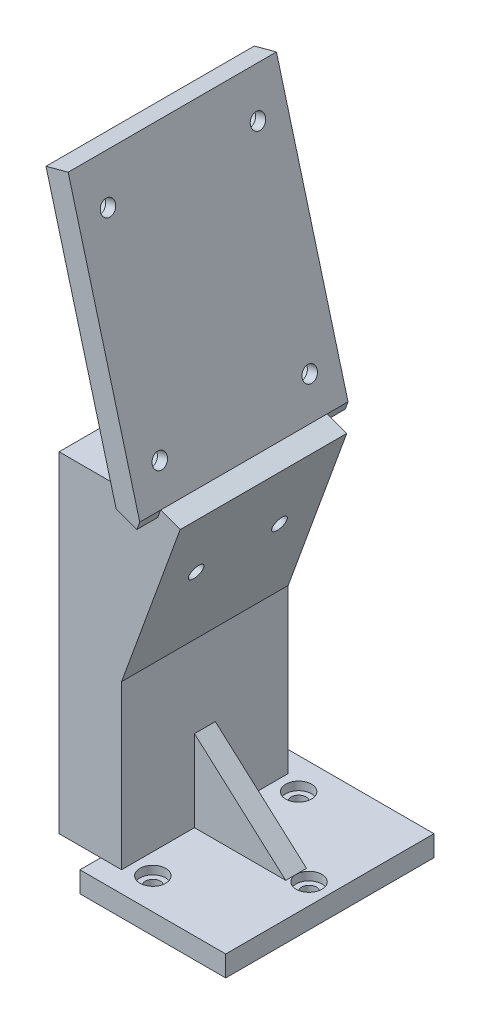
SolidWorks part; units mm, degrees
ref_plane "前视基准面" through (0, 0, 0) normal (0, 0, 1) x (1, 0, 0)
ref_plane "上视基准面" through (0, 0, 0) normal (0, 1, 0) x (1, 0, 0)
ref_plane "右视基准面" through (0, 0, 0) normal (1, 0, 0) x (0, 0, -1)
other "Configuration Table"
sketch "草图1" plane through (0, 0, 0) normal (0, 0, 1) x (1, 0, 0)
  line L0 (0, 0) -> (0, 45)
  line L1 (0, 45) -> (14.3648, 84.4671)
  dimension "D1" = 160
  dimension "D2" = 45
  dimension "D3" = 42
sketch "草图2" plane through (0, 0, 0) normal (0, 1, 0) x (1, 0, 0)
  line L1 (0, 20) -> (5, 20)
  line L2 (0, 20) -> (0, -20)
  line L3 (0, -20) -> (5, -20)
  line L4 (5, 20) -> (5, -20)
  point P4 (0, 0)
  dimension "D1" = 5
  dimension "D2" = 40
sweep "扫描1" add profiles "草图2" path "草图1"
sketch "草图3" plane through (-14.4627, 5.264, 0) normal (-0.9397, 0.342, 0) x (0, 0, 1)
  line L0 (-20, 66.2862) -> (20, 66.2862) construction
  line L1 (-20, 42.2862) -> (-20, 84.2862) construction
  line L2 (20, 42.2862) -> (20, 84.2862) construction
  line L3 (0, 77.3553) -> (0, -49922.6447) construction
  line L4 (-20, 84.2862) -> (20, 84.2862) construction
  line L5 (-10, 66.2862) -> (10, 66.2862) construction
  circle A0 centre (-10, 66.2862) radius 1.8
  circle A1 centre (10, 66.2862) radius 1.8
  point P10 (0, 84.2862)
  point P13 (0, 66.2862)
  dimension "D2" = 3.6
  dimension "D3" = 3.6
  dimension "D1" = 20
  dimension "D4" = 18
extrude "切除-拉伸1" cut sketch "草图3" against normal up to next
sketch "草图6" plane through (0, 0, 0) normal (0, -1, 0) x (1, 0, 0)
  line L0 (5, 20) -> (5, -20) construction
  line L1 (5, 20) -> (35, 20)
  line L2 (5, 20) -> (5, -20)
  line L3 (5, -20) -> (35, -20)
  line L4 (35, 20) -> (35, -20)
  line L5 (0, 20) -> (5, 20) construction
  line L6 (5, -20) -> (19.0633, -20) construction
  dimension "D1" = 30
extrude "凸台-拉伸1" add sketch "草图6" against normal blind 5
sketch "草图8" plane through (0, 0, 0) normal (0, -1, 0) x (1, 0, 0)
  line L0 (5, 20) -> (5, -20) construction
  line L1 (5, 20) -> (5, -20) construction
  line L2 (5, 0) -> (50005, 0) construction
  line L3 (10, 17.5) -> (10, -17.5) construction
  line L4 (10, 0) -> (30, 0) construction
  circle A0 centre (10, 17.5) radius 1.8
  circle A1 centre (10, -17.5) radius 1.8
  circle A2 centre (30, 0) radius 1.8
  point P4 (5, 0)
  point P7 (10, 0)
  dimension "D2" = 3.6
  dimension "D3" = 3.6
  dimension "D6" = 3.6
  dimension "D1" = 35
  dimension "D4" = 5
  dimension "D5" = 20
extrude "切除-拉伸2" cut sketch "草图8" against normal up to next
sketch "草图9" plane through (0, 0, 0) normal (0, -1, 0) x (1, 0, 0)
  line L0 (35, 0) -> (-49965, 0) construction
  line L1 (0, 20) -> (35, 20)
  line L2 (0, 20) -> (0, 25)
  line L3 (0, 25) -> (35, 25)
  line L4 (35, 20) -> (35, 25)
  line L5 (35, -20) -> (35, 20) construction
  line L6 (35, -20) -> (35, -25)
  line L7 (0, -25) -> (35, -25)
  line L8 (0, -20) -> (0, -25)
  line L9 (0, -20) -> (35, -20)
  point P9 (35, 0)
  dimension "D1" = 5
extrude "凸台-拉伸2" add sketch "草图9" against normal up to surface (5 mm away) up to face at (10, 5, 15.7)
sketch "草图10" plane through (0, 5, 0) normal (0, 1, 0) x (1, 0, 0)
  circle A0 centre (10, -17.5) radius 3.1
  circle A1 centre (10, 17.5) radius 3.1
  circle A2 centre (30, 0) radius 3.1
  dimension "D1" = 6.2
  dimension "D2" = 6.2
  dimension "D3" = 6.2
extrude "切除-拉伸3" cut sketch "草图10" against normal blind 2
sketch "草图11" plane through (-14.4627, 5.264, 0) normal (-0.9397, 0.342, 0) x (0, 0, 1)
  circle A0 centre (-10, 66.2862) radius 3.1
  circle A1 centre (10, 66.2862) radius 3.1
  dimension "D1" = 6.2
  dimension "D2" = 6.2
extrude "切除-拉伸4" cut sketch "草图11" against normal blind 2
sketch "草图15" plane through (0, 0, -20) normal (0, 0, -1) x (-1, 0, 0)
  line L0 (-8.6808, 84.4076) -> (-13.6808, 82.5877)
  line L1 (0, 5) -> (10, 5)
  line L2 (0, 5) -> (0, 45)
  line L3 (-8.6808, 84.4076) -> (10, 84.4076)
  line L4 (10, 5) -> (10, 84.4076)
  line L5 (0, 45) -> (-14.3648, 84.4671) construction
  line L6 (-13.6808, 82.5877) -> (0, 45)
  dimension "D1" = 40
  dimension "D2" = 5
  dimension "D3" = 10
extrude "凸台-拉伸4" add sketch "草图15" against normal blind 3
ref_plane "基准面2" through (0, 0, 0) normal (0, 0, -1) x (-1, 0, 0)
mirror "镜向2" about plane through (0, 0, 0) normal (0, 0, -1) of "凸台-拉伸4"
sketch "草图16" plane through (0, 0, 0) normal (0, 0, -1) x (-1, 0, 0)
  line L0 (-14.3648, 84.4671) -> (2.8243, 148.6177)
  line L1 (2.8243, 148.6177) -> (8.1424, 147.1927)
  line L2 (8.1424, 147.1927) -> (-8.6808, 84.4076)
  line L3 (10, 84.4076) -> (-8.6808, 84.4076) construction
  line L4 (-13.6808, 82.5877) -> (-14.3648, 84.4671) construction
  line L5 (-8.6808, 84.4076) -> (-13.6808, 82.5877) construction
  line L6 (-13.6808, 82.5877) -> (-14.3648, 84.4671)
  line L7 (-8.6808, 84.4076) -> (-13.6808, 82.5877)
  dimension "D1" = 65
  dimension "D2" = 75
extrude "凸台-拉伸5" add sketch "草图16" along normal blind 25 and the other way blind 25
sketch "草图17" plane through (34.5194, 9.2494, 0) normal (0.9659, 0.2588, 0) x (0, 0, -1)
  line L1 (-18, 86.371) -> (18, 86.371) construction
  line L2 (0, 144.4076) -> (0, -49855.5924) construction
  line L3 (-25, 144.2847) -> (25, 144.2847) construction
  line L5 (20, 77.871) -> (-20, 77.871) construction
  line L6 (-32.5, 77.871) -> (32.5, 77.871) construction
  line L7 (-32.5, 77.871) -> (-32.5, 142.871) construction
  line L8 (-32.5, 142.871) -> (32.5, 142.871) construction
  line L9 (32.5, 77.871) -> (32.5, 142.871) construction
  line L10 (-32.5, 77.871) -> (32.5, 142.871) construction
  line L11 (-32.5, 142.871) -> (32.5, 77.871) construction
  line L12 (-18, 86.371) -> (-18, 134.371) construction
  line L13 (-18, 134.371) -> (18, 134.371) construction
  line L14 (18, 86.371) -> (18, 134.371) construction
  line L15 (-18, 86.371) -> (18, 134.371) construction
  line L16 (-18, 134.371) -> (18, 86.371) construction
  circle A0 centre (-18, 134.371) radius 1.8
  circle A1 centre (18, 134.371) radius 1.8
  circle A2 centre (18, 86.371) radius 1.8
  circle A3 centre (-18, 86.371) radius 1.8
  point P0 (0, 110.371)
  point P7 (0, 144.2847)
  point P11 (0, 110.371)
  dimension "D3" = 3.6
  dimension "D6" = 3.6
  dimension "D7" = 3.6
  dimension "D1" = 48
  dimension "D2" = 36
  dimension "D4" = 65
  dimension "D5" = 65
extrude "切除-拉伸5" cut sketch "草图17" against normal up to next
sketch "草图18" plane through (29.2012, 7.8244, 0) normal (-0.9659, -0.2588, 0) x (0, 0, 1)
  circle A0 centre (-18, 134.371) radius 3.5
  circle A1 centre (18, 134.371) radius 3.5
  circle A2 centre (18, 86.371) radius 3.5
  circle A3 centre (-18, 86.371) radius 3.5
  dimension "D1" = 7
  dimension "D2" = 7
  dimension "D3" = 7
  dimension "D4" = 7
extrude "切除-拉伸6" cut sketch "草图18" against normal blind 3
sketch "草图19" plane through (0, 0, -17) normal (0, 0, 1) x (1, 0, 0)
  line L0 (12.6547, 79.7686) -> (8.1518, 81.4076)
  line L1 (8.1518, 81.4076) -> (-10, 81.4076)
  line L2 (-10, 84.4076) -> (-10, 81.4076)
  line L3 (13.6808, 82.5877) -> (12.6547, 79.7686)
  line L6 (0, 5) -> (0, 45)
  line L7 (0, 45) -> (13.6808, 82.5877)
  line L8 (13.6808, 82.5877) -> (8.6808, 84.4076)
  line L9 (8.6808, 84.4076) -> (-10, 84.4076)
  line L10 (-10, 84.4076) -> (-10, 5)
  line L11 (-10, 5) -> (0, 5)
  line L14 (13.6808, 82.5877) -> (8.6808, 84.4076)
  line L15 (8.6808, 84.4076) -> (-10, 84.4076)
  dimension "D1" = 0
  dimension "D2" = 3
extrude "凸台-拉伸6" add sketch "草图19" along normal up to surface (34 mm away) up to face at (0.3936, 51.0671, 17)
sketch "草图20" plane through (0, 0, 0) normal (0, 0, -1) x (-1, 0, 0)
  line L0 (10, 84.4076) -> (8.1424, 147.1927)
rib "筋4" sketch "草图20" sketch "草图20" thickness 5 extrusion direction parallel to sketch draft on no parameters "D1"=5
sketch "草图21" plane through (0, 0, 0) normal (0, 0, -1) x (-1, 0, 0)
  line L0 (-5, 24.5592) -> (-26.9, 5)
  line L1 (-5, 5) -> (-5, 44.1184) construction
  line L2 (-35, 5) -> (0, 5) construction
  point P6 (0, 0)
rib "筋5" sketch "草图21" sketch "草图21" thickness 5 extrusion direction parallel to sketch draft on no parameters "D1"=5
